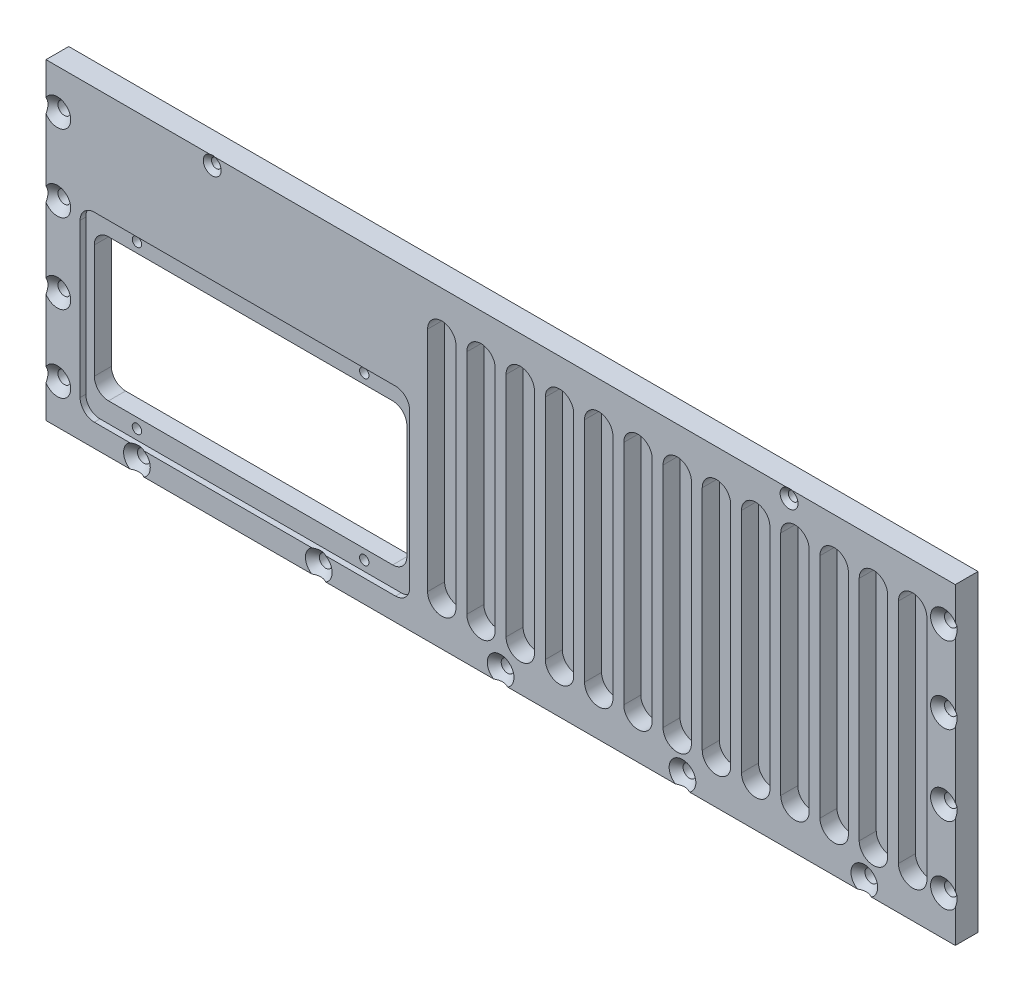
SolidWorks part; units mm, degrees
material "7079 Alloy"
ref_plane "Front Plane" through (0, 0, 0) normal (0, 0, 1) x (1, 0, 0)
ref_plane "Top Plane" through (0, 0, 0) normal (0, 1, 0) x (1, 0, 0)
ref_plane "Right Plane" through (0, 0, 0) normal (1, 0, 0) x (0, 0, -1)
sketch "Sketch1" plane through (0, 0, 0) normal (0, 0, 1) x (1, 0, 0)
  line L0 (-160, 0) -> (0, 0) construction
  line L1 (-160, 55) -> (160, 55)
  line L2 (-160, 55) -> (-160, -55)
  line L3 (-160, -55) -> (160, -55)
  line L4 (160, 55) -> (160, -55)
  line L5 (0, 0) -> (0, 55) construction
  dimension "D1" = 110
  dimension "D2" = 320
extrude "Extrude1" add sketch "Sketch1" along normal blind 8
sketch "Sketch2" plane through (0, 0, 8) normal (0, 0, 1) x (1, 0, 0)
  line L0 (156, 55) -> (156, -55) construction
  line L1 (160, 55) -> (-160, 55) construction
  line L2 (-160, -55) -> (160, -55) construction
  line L3 (0, 0) -> (0, 55) construction
  line L4 (0, 0) -> (160, 0) construction
  line L5 (160, -55) -> (160, 55) construction
  circle A0 centre (156, 41) radius 1.75
  circle A1 centre (156, 14) radius 1.75
  circle A2 centre (156, -41) radius 1.75
  circle A3 centre (156, -14) radius 1.75
  circle A4 centre (-156, -41) radius 1.75
  circle A5 centre (-156, -14) radius 1.75
  circle A6 centre (-156, 14) radius 1.75
  circle A7 centre (-156, 41) radius 1.75
  dimension "D2" = 3.5
  dimension "D4" = 27
  dimension "D1" = 4
  dimension "D3" = 14
extrude "Cut-Extrude1" cut sketch "Sketch2" against normal through all
sketch "Sketch6" plane through (0, 0, 8) normal (0, 0, 1) x (1, 0, 0)
  line L0 (160, 0) -> (145, 0) construction
  line L1 (160, -55) -> (160, 55) construction
  line L2 (145, 0) -> (145, 55) construction
  line L3 (160, 55) -> (-160, 55) construction
  line L4 (150, 40) -> (150, -40)
  line L5 (140, 40) -> (140, -40)
  line L6 (136.1905, 40) -> (136.1905, -40)
  line L58 (126.1905, 40) -> (126.1905, -40)
  line L59 (122.381, 40) -> (122.381, -40)
  line L60 (112.381, 40) -> (112.381, -40)
  line L61 (108.5714, 40) -> (108.5714, -40)
  line L62 (98.5714, 40) -> (98.5714, -40)
  line L63 (94.7619, 40) -> (94.7619, -40)
  line L64 (84.7619, 40) -> (84.7619, -40)
  line L65 (80.9524, 40) -> (80.9524, -40)
  line L66 (70.9524, 40) -> (70.9524, -40)
  line L67 (67.1429, 40) -> (67.1429, -40)
  line L68 (57.1429, 40) -> (57.1429, -40)
  line L69 (53.3333, 40) -> (53.3333, -40)
  line L70 (43.3333, 40) -> (43.3333, -40)
  line L71 (39.5238, 40) -> (39.5238, -40)
  line L72 (29.5238, 40) -> (29.5238, -40)
  line L73 (25.7143, 40) -> (25.7143, -40)
  line L74 (15.7143, 40) -> (15.7143, -40)
  line L75 (11.9048, 40) -> (11.9048, -40)
  line L76 (1.9048, 40) -> (1.9048, -40)
  line L77 (-1.9048, 40) -> (-1.9048, -40)
  line L78 (-11.9048, 40) -> (-11.9048, -40)
  line L79 (-15.7143, 40) -> (-15.7143, -40)
  line L80 (-25.7143, 40) -> (-25.7143, -40)
  arc A0 (150, 40) -> (140, 40) centre (145, 40) ccw
  arc A1 (150, -40) -> (140, -40) centre (145, -40) cw
  arc A52 (136.1905, 40) -> (126.1905, 40) centre (131.1905, 40) ccw
  arc A53 (136.1905, -40) -> (126.1905, -40) centre (131.1905, -40) cw
  arc A54 (122.381, 40) -> (112.381, 40) centre (117.381, 40) ccw
  arc A55 (122.381, -40) -> (112.381, -40) centre (117.381, -40) cw
  arc A56 (108.5714, 40) -> (98.5714, 40) centre (103.5714, 40) ccw
  arc A57 (108.5714, -40) -> (98.5714, -40) centre (103.5714, -40) cw
  arc A58 (94.7619, 40) -> (84.7619, 40) centre (89.7619, 40) ccw
  arc A59 (94.7619, -40) -> (84.7619, -40) centre (89.7619, -40) cw
  arc A60 (80.9524, 40) -> (70.9524, 40) centre (75.9524, 40) ccw
  arc A61 (80.9524, -40) -> (70.9524, -40) centre (75.9524, -40) cw
  arc A62 (67.1429, 40) -> (57.1429, 40) centre (62.1429, 40) ccw
  arc A63 (67.1429, -40) -> (57.1429, -40) centre (62.1429, -40) cw
  arc A64 (53.3333, 40) -> (43.3333, 40) centre (48.3333, 40) ccw
  arc A65 (53.3333, -40) -> (43.3333, -40) centre (48.3333, -40) cw
  arc A66 (39.5238, 40) -> (29.5238, 40) centre (34.5238, 40) ccw
  arc A67 (39.5238, -40) -> (29.5238, -40) centre (34.5238, -40) cw
  arc A68 (25.7143, 40) -> (15.7143, 40) centre (20.7143, 40) ccw
  arc A69 (25.7143, -40) -> (15.7143, -40) centre (20.7143, -40) cw
  arc A70 (11.9048, 40) -> (1.9048, 40) centre (6.9048, 40) ccw
  arc A71 (11.9048, -40) -> (1.9048, -40) centre (6.9048, -40) cw
  arc A72 (-1.9048, 40) -> (-11.9048, 40) centre (-6.9048, 40) ccw
  arc A73 (-1.9048, -40) -> (-11.9048, -40) centre (-6.9048, -40) cw
  arc A74 (-15.7143, 40) -> (-25.7143, 40) centre (-20.7143, 40) ccw
  arc A75 (-15.7143, -40) -> (-25.7143, -40) centre (-20.7143, -40) cw
  point P12 (150, 0)
  point P17 (140, 0)
  dimension "D2" = 5
  dimension "D1" = 15
  dimension "D3" = 80
  dimension "D5" = 13.8095
  dimension "D4" = 13
extrude "Cut-Extrude2" cut sketch "Sketch6" against normal blind 6
sketch "Sketch7" plane through (0, 0, 8) normal (0, 0, 1) x (1, 0, 0)
  line L0 (-152, -55) -> (-152, -51) construction
  line L1 (-160, -55) -> (160, -55) construction
  line L2 (-152, -51) -> (0, -51) construction
  line L4 (-160, 55) -> (-160, -55) construction
  line L5 (0, -51) -> (0, -55) construction
  circle A0 centre (-64, -51) radius 2.25
  circle A1 centre (0, -51) radius 2.25
  circle A2 centre (64, -51) radius 2.25
  circle A3 centre (-128, -51) radius 2.25
  circle A4 centre (128, -51) radius 2.25
  dimension "D4" = 4.5
  dimension "D1" = 8
  dimension "D2" = 4
  dimension "D6" = 24
  dimension "D3" = 5
extrude "Cut-Extrude3" cut sketch "Sketch7" against normal blind 10
sketch "Sketch10" plane through (0, 0, 8) normal (0, 0, 1) x (1, 0, 0)
  line L0 (160, -55) -> (160, 55) construction
  line L2 (0, 55) -> (0, -55) construction
  line L3 (160, 55) -> (-160, 55) construction
  line L4 (-160, -55) -> (160, -55) construction
  circle A0 centre (101.5, 52) radius 1.5
  circle A1 centre (-101.5, 52) radius 1.5
  dimension "D1" = 58.5
  dimension "D2" = 3
  dimension "D3" = 3
extrude "Cut-Extrude4" cut sketch "Sketch10" against normal blind 10
hole_wizard "CSK for M3 Flat Head Machine Screw3" positions "Sketch12" profile "Sketch11" countersink size "M3" standard "Ansi Metric" end condition through all
sketch "Sketch12" plane through (0, 0, 8) normal (0, 0, 1) x (1, 0, 0)
  point P1 (-101.5, 52)
  point P4 (101.5, 52)
sketch "Sketch11" plane through (-101.5, 52, 8) normal (1, 0, 0) x (0, -1, 0)
  line L0 (0, 0) -> (0, 8)
  line L1 (0, 8) -> (1.7, 8)
  line L2 (1.7, 8) -> (1.7, 1.45)
  line L3 (1.7, 1.45) -> (3.15, 0)
  line L5 (3.15, 0) -> (0, 0)
  line L6 (-1.7, 1.45) -> (-3.15, 0) construction
  line L11 (0, -6.35) -> (0, 107.95) construction
  dimension "Thru Hole Dia." = 3.4
  dimension "Thru Hole Depth" = 8
  dimension "Near C'Sink Dia." = 6.3
  dimension "Near C'Sink Angle" = 90
sketch "Sketch13" plane through (0, 0, 8) normal (0, 0, 1) x (1, 0, 0)
  line L0 (-160, 55) -> (-160, -55) construction
  line L1 (-145, -40) -> (-35, -40)
  line L2 (-145, -40) -> (-145, 10)
  line L3 (-145, 10) -> (-35, 10)
  line L4 (-35, -40) -> (-35, 10)
  line L5 (-160, -55) -> (160, -55) construction
  dimension "D1" = 50
  dimension "D2" = 110
  dimension "D3" = 15
  dimension "D4" = 15
extrude "Cut-Extrude5" cut sketch "Sketch13" against normal blind 10
sketch "Sketch14" plane through (0, 0, 8) normal (0, 0, 1) x (1, 0, 0)
  line L0 (-160, 55) -> (-160, -55) construction
  line L1 (-32, 17) -> (-148, 17)
  line L2 (-32, 17) -> (-32, -47)
  line L3 (-32, -47) -> (-148, -47)
  line L4 (-148, 17) -> (-148, -47)
  line L5 (-35, 10) -> (-145, 10) construction
  line L6 (-35, -40) -> (-35, 10) construction
  line L8 (-160, -55) -> (160, -55) construction
  dimension "D1" = 12
  dimension "D2" = 8
  dimension "D3" = 7
  dimension "D4" = 3
extrude "Cut-Extrude6" cut sketch "Sketch14" against normal blind 2
fillet "Fillet1" radius 5 8 edges at (-35, -40, 3) (-35, 10, 3) (-145, 10, 3) (-145, -40, 3) (-32, 17, 7) (-148, 17, 7) (-148, -47, 7) (-32, -47, 7)
sketch "Sketch16" plane through (0, 0, 6) normal (0, 0, 1) x (1, 0, 0)
  line L0 (-90, -40) -> (-90, 10) construction
  line L1 (-140, -40) -> (-40, -40) construction
  line L2 (-40, 10) -> (-140, 10) construction
  line L3 (-145, -15) -> (-35, -15) construction
  line L4 (-145, 5) -> (-145, -35) construction
  line L5 (-35, -35) -> (-35, 5) construction
  circle A0 centre (-130, -43.5) radius 1.65
  circle A1 centre (-50, -43.5) radius 1.65
  circle A2 centre (-50, 13.5) radius 1.65
  circle A3 centre (-130, 13.5) radius 1.65
  dimension "D1" = 3.3
  dimension "D2" = 40
  dimension "D3" = 3.5
extrude "Cut-Extrude7" cut sketch "Sketch16" against normal blind 10
hole_wizard "CSK for M4 Flat Head Machine Screw1" positions "Sketch5" profile "Sketch4" countersink size "M4" standard "Ansi Metric" end condition through all
sketch "Sketch5" plane through (0, 0, 8) normal (0, 0, 1) x (1, 0, 0)
  point P1 (156, 41)
  point P4 (156, 14)
  point P11 (156, -41)
  point P14 (-156, -41)
  point P17 (-156, -14)
  point P20 (-156, 14)
  point P23 (-156, 41)
  point P30 (156, -14)
  point P34 (-128, -51)
  point P37 (-64, -51)
  point P40 (0, -51)
  point P43 (64, -51)
  point P46 (128, -51)
sketch "Sketch4" plane through (156, 41, 8) normal (1, 0, 0) x (0, -1, 0)
  line L0 (0, 0) -> (0, 8)
  line L1 (0, 8) -> (2.25, 8)
  line L2 (2.25, 8) -> (2.25, 2.45)
  line L3 (2.25, 2.45) -> (4.7, 0)
  line L5 (4.7, 0) -> (0, 0)
  line L6 (-2.25, 2.45) -> (-4.7, 0) construction
  line L11 (0, -6.35) -> (0, 107.95) construction
  dimension "Thru Hole Dia." = 4.5
  dimension "Thru Hole Depth" = 8
  dimension "Near C'Sink Dia." = 9.4
  dimension "Near C'Sink Angle" = 90
